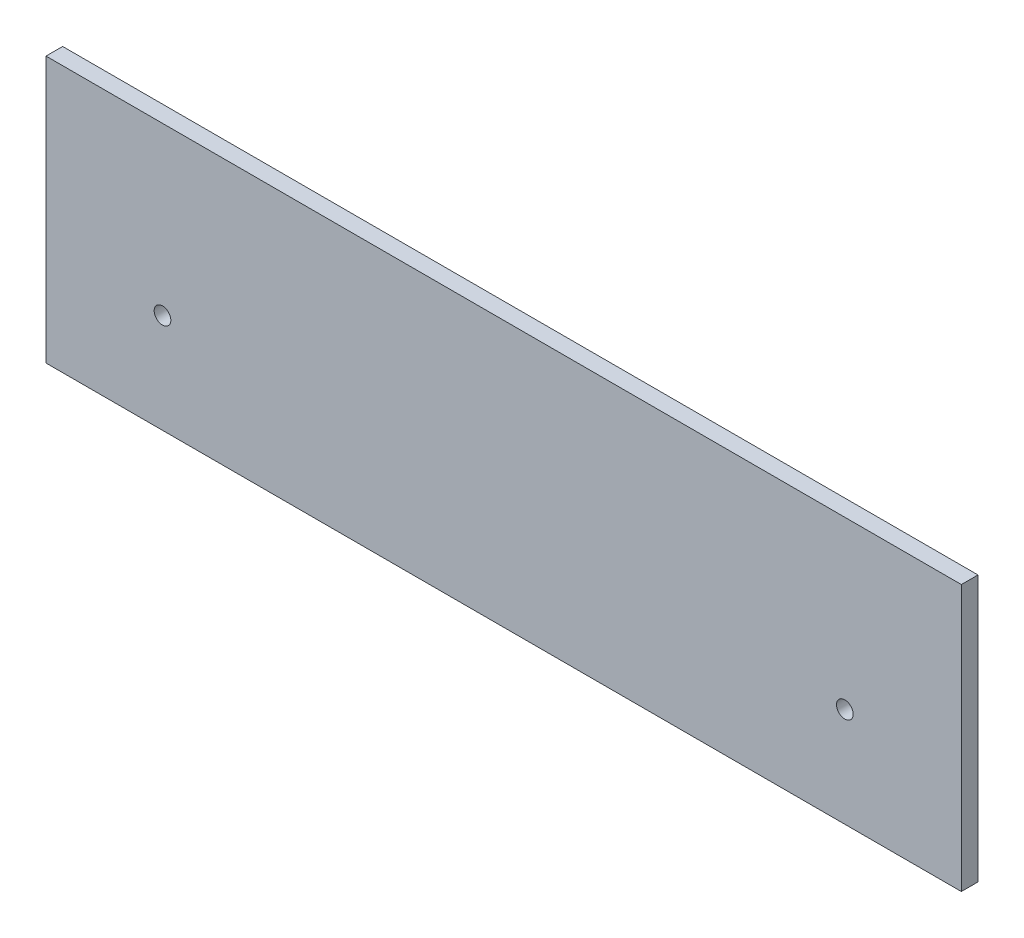
SolidWorks part; units mm, degrees
ref_plane "Front Plane" through (0, 0, 0) normal (0, 0, 1) x (1, 0, 0)
ref_plane "Top Plane" through (0, 0, 0) normal (0, 1, 0) x (1, 0, 0)
ref_plane "Right Plane" through (0, 0, 0) normal (1, 0, 0) x (0, 0, -1)
sketch "Sketch1" plane through (0, 0, 0) normal (0, 0, 1) x (1, 0, 0)
  line L1 (0, 0) -> (55, 0)
  line L2 (0, 0) -> (0, -20)
  line L3 (0, -20) -> (55, -20)
  line L4 (55, 0) -> (55, -20)
  dimension "D1" = 55
  dimension "D2" = 20
extrude "Boss-Extrude1" add sketch "Sketch1" along normal blind 1
sketch "Sketch2" plane through (0, 0, 1) normal (0, 0, 1) x (1, 0, 0)
  line L0 (0, 0) -> (0, -20) construction
  circle A0 centre (7, -10) radius 0.5
  point P2 (0, 0)
  point P5 (1, -11.0881)
  point P6 (5.8007, -10.2874)
  point P7 (0, 0)
  point P8 (6, -17.568)
  point P9 (1, -18.8307)
  point P10 (0, -10)
  dimension "D1" = 1
  dimension "D2" = 7
extrude "Cut-Extrude1" cut sketch "Sketch2" against normal through all
ref_plane "Plane2" through (27.5, 0, 0) normal (-1, 0, 0) x (0, 0, 1)
mirror "Mirror2" about plane through (27.5, 0, 0) normal (-1, 0, 0) of "Cut-Extrude1"
sketch "Sketch4" plane through (0, 0, 1) normal (0, 0, 1) x (1, 0, 0)
  line L0 (0, 0) -> (0, -20) construction
  line L1 (0, -15.9756) -> (55, -15.9756)
  line L2 (0, -15.9756) -> (0, -20)
  line L3 (0, -20) -> (55, -20)
  line L4 (55, -15.9756) -> (55, -20)
  line L5 (0, -20) -> (55, -20) construction
  line L6 (55, -20) -> (55, 0) construction
  dimension "D1" = 4.0244
extrude "Cut-Extrude3" cut sketch "Sketch4" against normal blind 5
